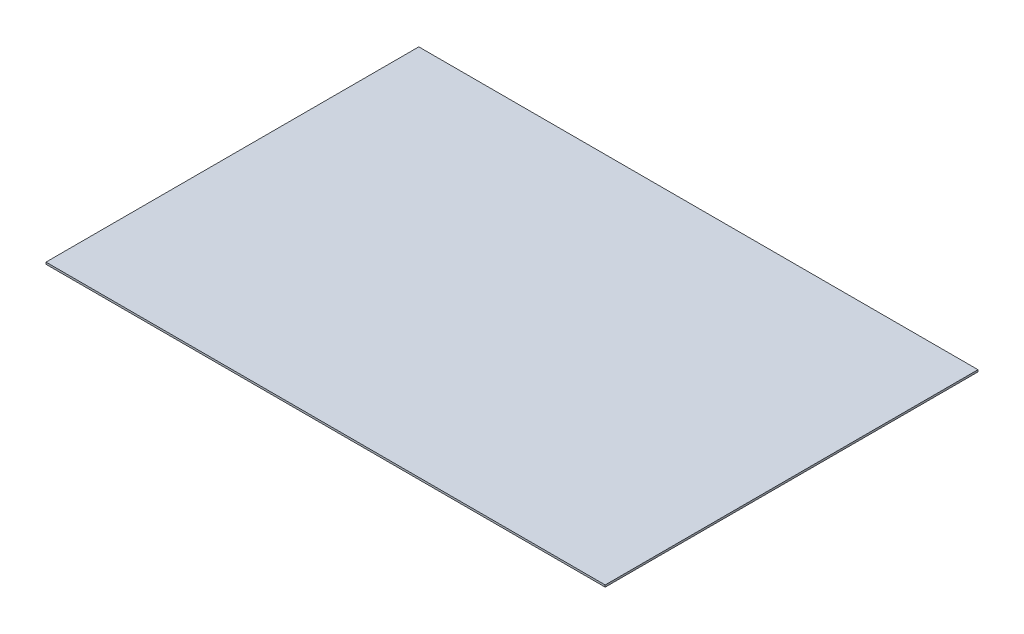
SolidWorks part; units mm, degrees
ref_plane "Front" through (0, 0, 0) normal (0, 0, 1) x (1, 0, 0)
ref_plane "Top" through (0, 0, 0) normal (0, 1, 0) x (1, 0, 0)
ref_plane "Right" through (0, 0, 0) normal (1, 0, 0) x (0, 0, -1)
sketch "Sketch1" plane through (0, 0, 0) normal (0, 1, 0) x (1, 0, 0)
  line L1 (-914.4, 609.6) -> (914.4, 609.6)
  line L2 (-914.4, 609.6) -> (-914.4, -609.6)
  line L3 (-914.4, -609.6) -> (914.4, -609.6)
  line L4 (914.4, 609.6) -> (914.4, -609.6)
  line L5 (-914.4, 609.6) -> (914.4, -609.6) construction
  line L6 (-914.4, -609.6) -> (914.4, 609.6) construction
  point P0 (0, 0)
  dimension "D1" = 1219.2
  dimension "D2" = 1828.8
extrude "Boss-Extrude1" add sketch "Sketch1" along normal blind 6.35
